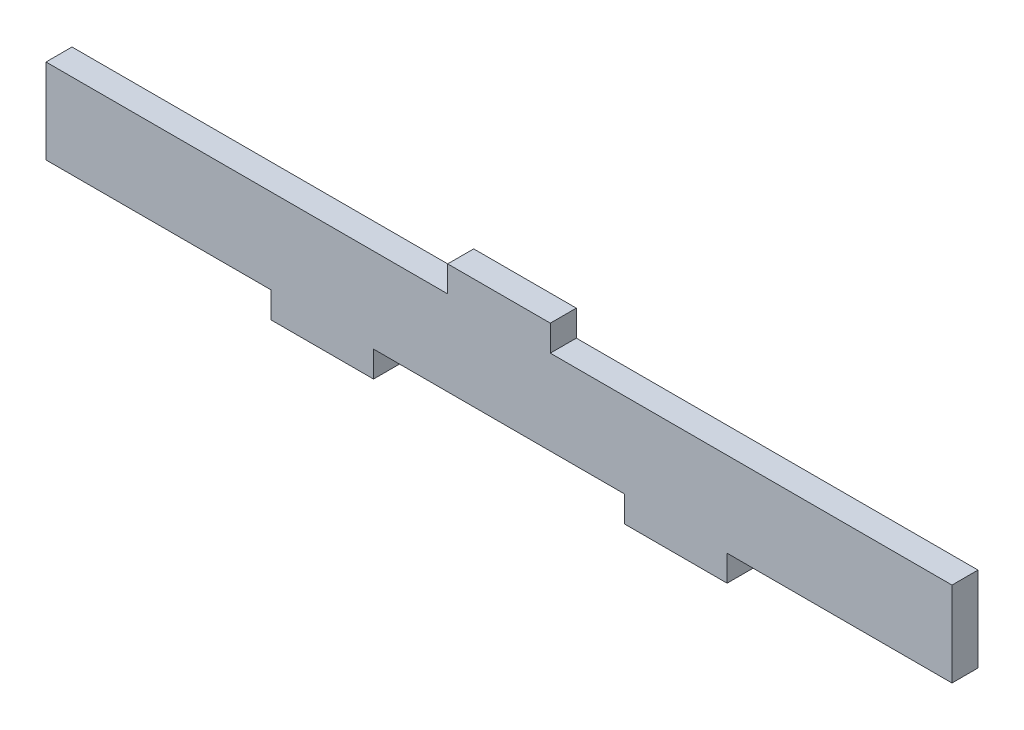
SolidWorks part; units mm, degrees
ref_plane "Front Plane" through (0, 0, 0) normal (0, 0, 1) x (1, 0, 0)
ref_plane "Top Plane" through (0, 0, 0) normal (0, 1, 0) x (1, 0, 0)
ref_plane "Right Plane" through (0, 0, 0) normal (1, 0, 0) x (0, 0, -1)
sketch "Sketch1" plane through (0, 0, 0) normal (0, 0, 1) x (1, 0, 0)
  line L1 (0, 0) -> (177.8, 0)
  line L2 (0, 0) -> (0, 25.4)
  line L3 (0, 25.4) -> (177.8, 25.4)
  line L4 (177.8, 0) -> (177.8, 25.4)
  dimension "D1" = 177.8
  dimension "D2" = 25.4
extrude "Boss-Extrude1" add sketch "Sketch1" along normal blind 4.826
sketch "Sketch2" plane through (0, 0, 4.826) normal (0, 0, 1) x (1, 0, 0)
  line L1 (0, 0) -> (177.8, 0) construction
  line L2 (0, 0) -> (46.5667, 0)
  line L3 (0, 0) -> (0, 4.826)
  line L4 (0, 4.826) -> (46.5667, 4.826)
  line L5 (46.5667, 0) -> (46.5667, 4.826)
  line L6 (65.6167, 0) -> (112.1833, 0)
  line L7 (65.6167, 0) -> (65.6167, 4.826)
  line L8 (65.6167, 4.826) -> (112.1833, 4.826)
  line L9 (112.1833, 0) -> (112.1833, 4.826)
  line L11 (46.5667, 4.826) -> (65.6167, 4.826) construction
  line L12 (177.8, 0) -> (131.2333, 0)
  line L14 (177.8, 0) -> (177.8, 4.826)
  line L15 (177.8, 4.826) -> (131.2333, 4.826)
  line L16 (131.2333, 0) -> (131.2333, 4.826)
  line L17 (112.1833, 4.826) -> (131.2333, 4.826) construction
  dimension "D1" = 19.05
  dimension "D2" = 4.826
extrude "Bottom Edge Slots" cut sketch "Sketch2" against normal through all
sketch "Sketch3" plane through (0, 0, 4.826) normal (0, 0, 1) x (1, 0, 0)
  line L0 (79.375, 20.574) -> (98.425, 20.574) construction
  line L1 (0, 25.4) -> (79.375, 25.4)
  line L2 (0, 25.4) -> (0, 20.574)
  line L3 (0, 20.574) -> (79.375, 20.574)
  line L4 (79.375, 25.4) -> (79.375, 20.574)
  line L5 (177.8, 25.4) -> (98.425, 25.4)
  line L6 (177.8, 25.4) -> (177.8, 20.574)
  line L7 (177.8, 20.574) -> (98.425, 20.574)
  line L8 (98.425, 25.4) -> (98.425, 20.574)
  dimension "D1" = 19.05
  dimension "D2" = 4.826
extrude "Top Edge Slots" cut sketch "Sketch3" against normal through all
sketch "Sketch4" plane through (0, 0, 4.826) normal (0, 0, 1) x (1, 0, 0)
  line L0 (46.5667, 4.826) -> (0, 4.826) construction
  line L1 (0, 20.574) -> (4.826, 20.574)
  line L2 (0, 20.574) -> (0, 4.826)
  line L3 (0, 4.826) -> (4.826, 4.826)
  line L4 (4.826, 20.574) -> (4.826, 4.826)
  line L5 (177.8, 4.826) -> (131.2333, 4.826) construction
  line L6 (177.8, 20.574) -> (172.974, 20.574)
  line L7 (177.8, 20.574) -> (177.8, 4.826)
  line L8 (177.8, 4.826) -> (172.974, 4.826)
  line L9 (172.974, 20.574) -> (172.974, 4.826)
  dimension "D1" = 4.826
extrude "Edge Cuts" cut sketch "Sketch4" against normal through all
equation "\"material\"= \"gmaterial@Forklift_Assembly.assembly\""
equation "\"D1@Boss-Extrude1\"=\"material\""
equation "\"D2@Sketch2\"=\"material\""
equation "\"D2@Sketch3\"=\"material\""
equation "\"D1@Sketch4\"=\"\"material\""
